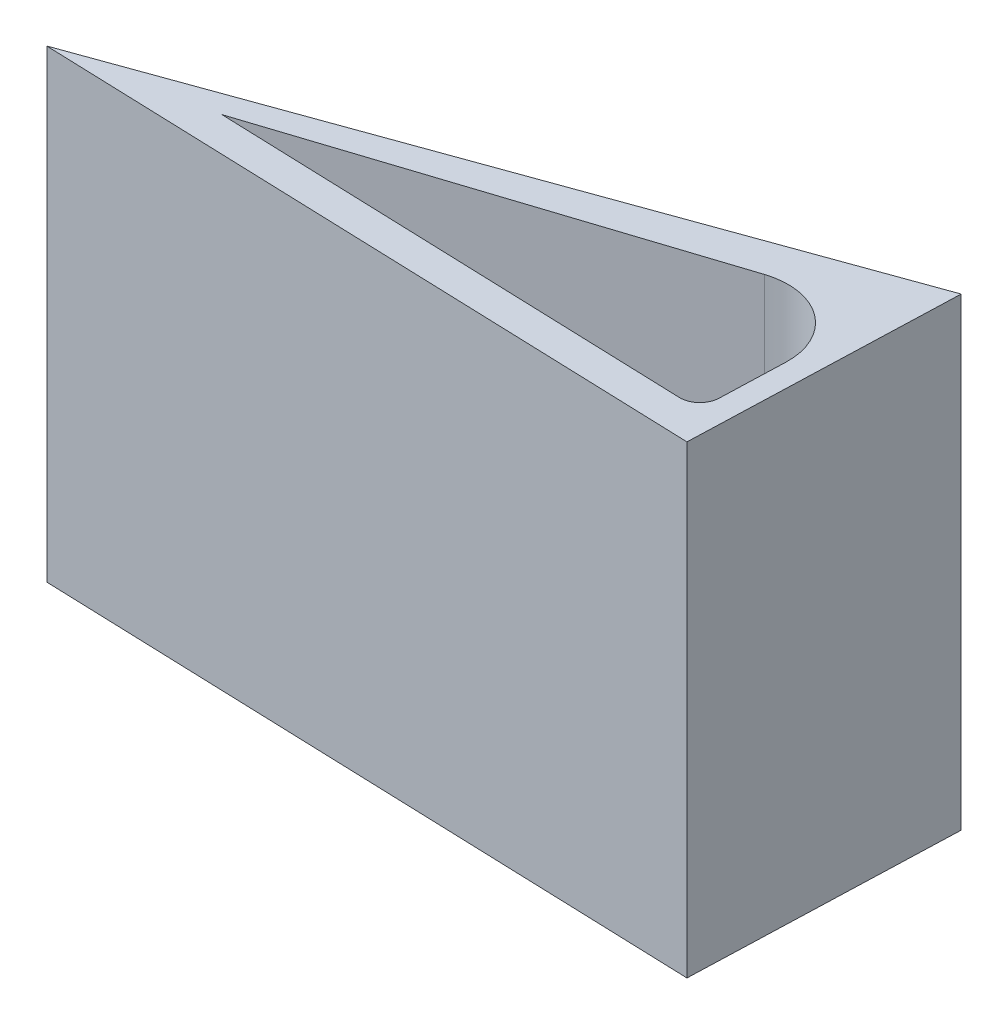
SolidWorks part; units mm, degrees
ref_plane "前视基准面" through (0, 0, 0) normal (0, 0, 1) x (1, 0, 0)
ref_plane "上视基准面" through (0, 0, 0) normal (0, 1, 0) x (1, 0, 0)
ref_plane "右视基准面" through (0, 0, 0) normal (1, 0, 0) x (0, 0, -1)
other "Configuration Table"
sketch "草图5" plane through (0, 0, 0) normal (0, 1, 0) x (1, 0, 0)
  line L0 (0, 0) -> (99.9411, -3.4321)
  line L1 (99.9411, -3.4321) -> (101.3139, 36.5443)
  line L2 (101.3139, 36.5443) -> (0, 0)
extrude "凸台-拉伸2" add sketch "草图5" along normal blind 70
sketch "草图8" plane through (0, 0, 0) normal (0, -1, 0) x (1, 0, 0)
  line L0 (99.9411, 3.4321) -> (100.1127, -1.5649) construction
  line L1 (99.9411, 3.4321) -> (101.3139, -36.5443) construction
  line L2 (100.1127, -1.5649) -> (22.1586, -4.242) construction
  line L3 (96.559, -1.687) -> (97.4857, -28.6711) construction
  line L4 (97.4857, -28.6711) -> (22.1586, -4.242) construction
  line L5 (97.4857, -28.6711) -> (96.559, -1.687)
  line L6 (22.1586, -4.242) -> (97.4857, -28.6711)
  line L7 (22.1586, -4.242) -> (96.559, -1.687)
extrude "切除-拉伸1" cut sketch "草图8" against normal through all
fillet "圆角1" radius 10 1 edges at (97.4857, 35, -28.6711)
fillet "圆角2" radius 3 1 edges at (96.559, 35, -1.687)
